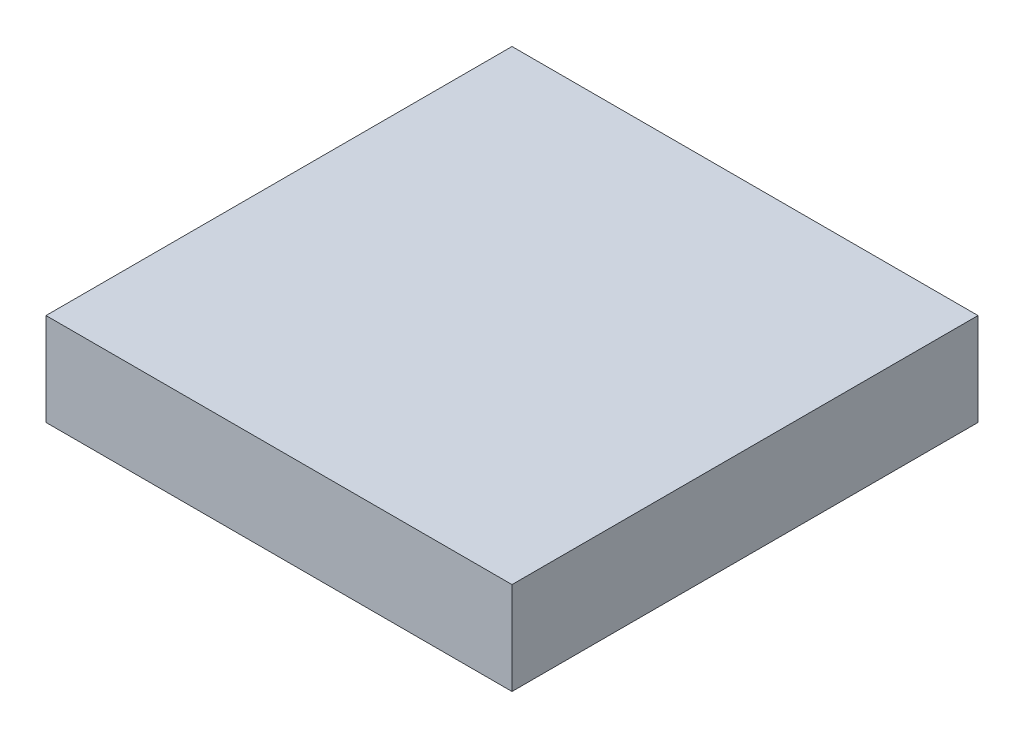
SolidWorks part; units mm, degrees
ref_plane "Front Plane" through (0, 0, 0) normal (0, 0, 1) x (1, 0, 0)
ref_plane "Top Plane" through (0, 0, 0) normal (0, 1, 0) x (1, 0, 0)
ref_plane "Right Plane" through (0, 0, 0) normal (1, 0, 0) x (0, 0, -1)
sketch "Sketch1" plane through (0, 0, 0) normal (0, 1, 0) x (1, 0, 0)
  line L1 (-7.925, 7.925) -> (7.925, 7.925)
  line L2 (-7.925, 7.925) -> (-7.925, -7.925)
  line L3 (-7.925, -7.925) -> (7.925, -7.925)
  line L4 (7.925, 7.925) -> (7.925, -7.925)
  line L5 (-7.925, 7.925) -> (7.925, -7.925) construction
  line L6 (-7.925, -7.925) -> (7.925, 7.925) construction
  point P0 (0, 0)
  dimension "D1" = 15.85
  dimension "D2" = 15.85
extrude "Boss-Extrude1" add sketch "Sketch1" against normal blind 3.15
shell "Shell1" thickness 1.5
sketch "Sketch2" plane through (0, -1.5, 0) normal (0, -1, 0) x (1, 0, 0)
  circle A0 centre (0, 0) radius 3.225
  circle A1 centre (0, 0) radius 2.425
  dimension "D1" = 6.45
  dimension "D2" = 4.85
extrude "Boss-Extrude2" add sketch "Sketch2" along normal offset from surface (1.45 mm away) 0.2 up to face at (0, -3.15, 0)
